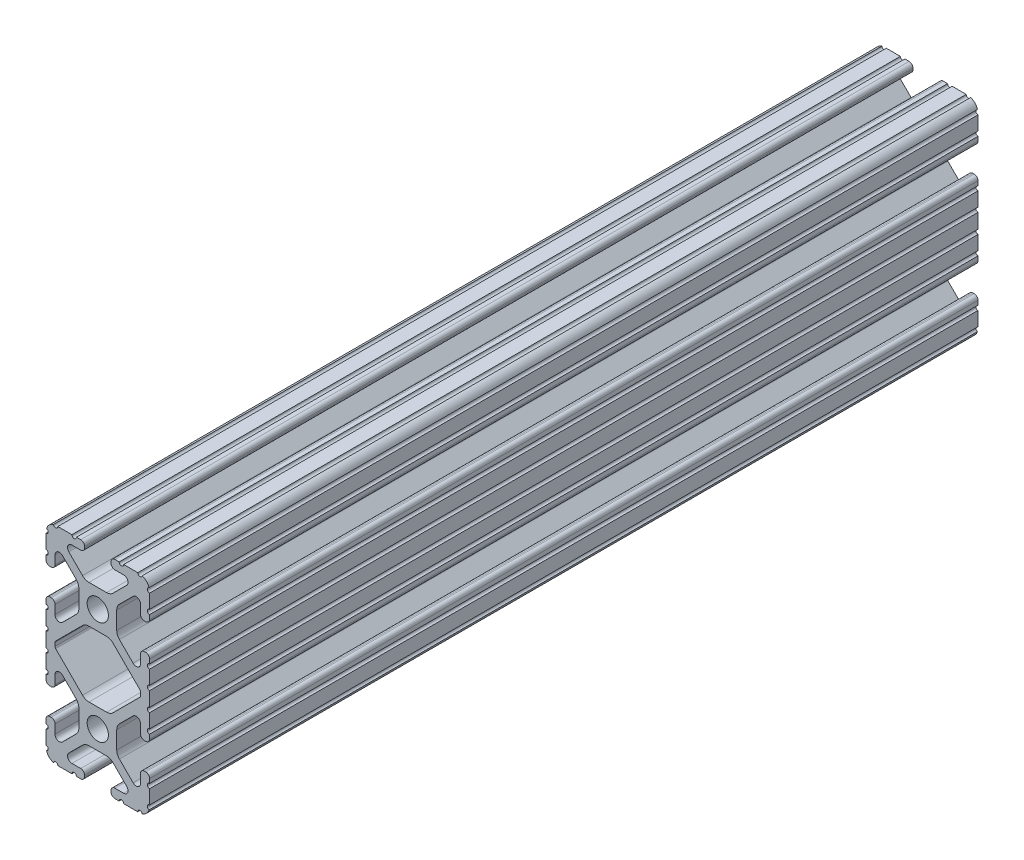
SolidWorks part; units mm, degrees
ref_plane "Front Plane" through (0, 0, 0) normal (0, 0, 1) x (1, 0, 0)
ref_plane "Top Plane" through (0, 0, 0) normal (0, 1, 0) x (1, 0, 0)
ref_plane "Right Plane" through (0, 0, 0) normal (1, 0, 0) x (0, 0, -1)
sketch "Sketch2" plane through (0, 0, 0) normal (0, 0, 1) x (1, 0, 0)
  line L0 (0, 25.4) -> (0, -25.4) construction
  line L1 (-12.7, 0) -> (12.7, 0) construction
  line L2 (3.2512, -25.4) -> (12.7, -25.4)
  line L3 (12.7, -25.4) -> (12.7, -15.9512)
  line L4 (3.2512, -25.4) -> (3.2512, -23.1902)
  line L5 (3.2512, -23.1902) -> (8.9276, -23.1902)
  line L6 (8.9276, -23.1902) -> (3.0856, -17.3482)
  line L7 (0, -12.7) -> (12.7, -25.4) construction
  line L8 (12.7, -15.9512) -> (10.4902, -15.9512)
  line L9 (10.4902, -15.9512) -> (10.4902, -21.6276)
  line L10 (10.4902, -21.6276) -> (4.6482, -15.7856)
  circle A0 centre (0, -12.7) radius 2.6035
  arc A1 (6.3485, -23.1902) -> (7.1039, -21.3665) centre (6.3485, -22.1219) ccw construction
  point P8 (0, -17.3482)
  dimension "Center Hole Diameter" = 5.207
  dimension "Rail Height" = 50.8
  dimension "Rail Width" = 25.4
  dimension "T-Slot Width" = 6.5024
  dimension "Slot Inner Width" = 14.8336
  dimension "Thickness" = 2.2098
  dimension "Slot Depth" = 5.842
  dimension "D1" = 2.2098
  dimension "C to C" = 25.4
sketch "Sketch3" plane through (0, 0, 0) normal (1, 0, 0) x (0, 0, -1)
  line L0 (-152.4, -25.4) -> (152.4, -25.4) construction
  line L1 (-127, 0) -> (127, 0) construction
  dimension "Length" = 304.8
  dimension "D1" = 25.4
sketch "Sketch4" plane through (0, 0, 0) normal (0, 0, 1) x (1, 0, 0)
  line L0 (4.1904, -25.4) -> (10.1173, -25.4)
  line L1 (3.2512, -25.4) -> (12.7, -25.4) construction
  line L2 (3.2512, -25.4) -> (3.2512, -23.1902) construction
  line L3 (3.2512, -23.1902) -> (8.9276, -23.1902) construction
  line L4 (3.2512, -24.1294) -> (3.2512, -24.4608)
  line L5 (4.1904, -23.1902) -> (6.3485, -23.1902)
  line L6 (0, -17.3482) -> (2.164, -17.3482)
  line L7 (8.9276, -23.1902) -> (3.0856, -17.3482) construction
  line L8 (3.7373, -17.9999) -> (7.1039, -21.3665)
  line L9 (12.7, -25.4) -> (12.7, -15.9512) construction
  line L10 (10.4902, -21.6276) -> (4.6482, -15.7856) construction
  line L11 (10.4902, -15.9512) -> (10.4902, -21.6276) construction
  line L12 (10.4902, -19.0485) -> (10.4902, -16.8904)
  line L13 (12.7, -15.9512) -> (10.4902, -15.9512) construction
  line L14 (11.4294, -15.9512) -> (11.7608, -15.9512)
  line L15 (12.7, -16.8904) -> (12.7, -22.8173)
  line L16 (8.6665, -19.8039) -> (5.2999, -16.4373)
  line L17 (4.6482, -12.7) -> (4.6482, -14.864)
  line L19 (0, -17.3482) -> (0, -15.3035)
  line L20 (0, 25.4) -> (0, -25.4) construction
  line L21 (4.6482, -12.7) -> (2.6035, -12.7)
  arc A0 (3.2512, -24.4608) -> (4.1904, -25.4) centre (4.1904, -24.4608) ccw
  circle A1 centre (0, -12.7) radius 2.6035 construction
  arc A2 (3.2512, -24.1294) -> (4.1904, -23.1902) centre (4.1904, -24.1294) cw
  arc A3 (6.3485, -23.1902) -> (7.1039, -21.3665) centre (6.3485, -22.1219) ccw
  arc A4 (2.164, -17.3482) -> (3.7373, -17.9999) centre (2.164, -19.5732) cw
  arc A5 (10.1173, -25.4) -> (12.7, -22.8173) centre (10.1173, -22.8173) ccw
  arc A6 (8.6665, -19.8039) -> (10.4902, -19.0485) centre (9.4219, -19.0485) ccw
  arc A7 (10.4902, -16.8904) -> (11.4294, -15.9512) centre (11.4294, -16.8904) cw
  arc A8 (11.7608, -15.9512) -> (12.7, -16.8904) centre (11.7608, -16.8904) cw
  arc A9 (5.2999, -16.4373) -> (4.6482, -14.864) centre (6.8732, -14.864) cw
  arc A11 (0, -15.3035) -> (2.6035, -12.7) centre (0, -12.7) ccw
  dimension "D1" = 2.5827
  dimension "D2" = 2.225
  dimension "D3" = 0.9392
extrude "Boss-Extrude1" add sketch "Sketch4" along normal mid plane 304.8
sketch "Sketch5" plane through (0, 0, 0) normal (0, 0, 1) x (1, 0, 0)
  line L0 (3.2512, -25.4) -> (12.7, -25.4) construction
  line L1 (4.1904, -23.1902) -> (6.3485, -23.1902) construction
  line L3 (0, -12.7) -> (12.7, -25.4) construction
  line L4 (6.3485, -23.1902) -> (6.3485, -25.4) construction
  line L5 (8.9276, -23.1902) -> (3.0856, -17.3482) construction
  circle A0 centre (10.3562, -25.4) radius 0.5524
  circle A1 centre (5.796, -25.4) radius 0.5524
  circle A2 centre (12.7, -23.0562) radius 0.5524
  circle A3 centre (12.7, -18.496) radius 0.5524
  point P10 (5.2694, -23.1902)
  point P12 (9.4219, -19.0485)
  dimension "D1" = 1.1049
extrude "Cut-Extrude1" cut sketch "Sketch5" against normal through all both and the other way through all
mirror "Mirror1" about plane through (4.6482, -12.7, 152.4) normal (0, -1, 0) of bodies 137 134
sketch "Sketch6" plane through (0, 0, 0) normal (0, 0, 1) x (1, 0, 0)
  line L0 (12.7, -1.7914) -> (12.7, 0)
  line L1 (12.7, 0) -> (9.8037, 0)
  line L2 (-12.7, 0) -> (12.7, 0) construction
  line L3 (9.8037, 0) -> (9.8037, -2.3438)
  line L4 (9.8037, -2.3438) -> (12.1476, -2.3438)
  circle A0 centre (12.7, -2.3438) radius 0.5524 construction
  arc A1 (12.7, -1.7914) -> (12.1476, -2.3438) centre (12.7, -2.3438) ccw
  arc A4 (12.58, -1.8046) -> (12.7, -2.8963) centre (12.7, -2.3438) ccw construction
  arc A6 (9.8037, 0) -> (10.8954, -0.12) centre (10.3562, 0) ccw construction
extrude "Boss-Extrude2" add sketch "Sketch6" along normal mid plane 304.8
sketch "Sketch7" plane through (0, 0, 0) normal (0, 0, 1) x (1, 0, 0)
  line L0 (5.4206, -5.7168) -> (10.3284, -0.809)
  line L1 (3.7373, -7.4001) -> (7.1039, -4.0335) construction
  line L2 (10.4902, -0.4184) -> (10.4902, 0)
  line L3 (0, 0) -> (10.4902, 0)
  line L4 (-12.7, 0) -> (12.7, 0) construction
  line L5 (0, 0) -> (5.4206, -5.7168)
  arc A0 (10.3284, -0.809) -> (10.4902, -0.4184) centre (9.9377, -0.4184) ccw
  arc A3 (12.7, -1.7914) -> (12.7, -2.8963) centre (12.7, -2.3438) ccw construction
extrude "Cut-Extrude2" cut sketch "Sketch7" against normal through all both and the other way through all
mirror "Mirror2" about plane through (0, 0, 0) normal (0, 1, 0) of bodies 139 135
mirror "Mirror3" about plane through (0, 0, 0) normal (1, 0, 0) of bodies 136
sketch "Sketch8" plane through (12.7, 0, 0) normal (1, 0, 0) x (0, 0, -1)
  line L0 (152.4, -25.4) -> (-152.4, -25.4) construction
  line L1 (-152.4, 25.4) -> (-101.6, 25.4)
  line L2 (-152.4, 25.4) -> (-152.4, -25.4)
  line L3 (-152.4, -25.4) -> (-101.6, -25.4)
  line L4 (-101.6, 25.4) -> (-101.6, -25.4)
  line L5 (152.4, 25.4) -> (-152.4, 25.4) construction
  line L6 (152.4, -25.4) -> (101.6, -25.4)
  line L7 (152.4, -25.4) -> (152.4, 25.4)
  line L8 (152.4, 25.4) -> (101.6, 25.4)
  line L9 (101.6, -25.4) -> (101.6, 25.4)
  dimension "D1" = 50.8
  dimension "D2" = 50.8
extrude "Cut-Extrude3" cut sketch "Sketch8" against normal through all
equation "\"D1@Boss-Extrude1\"=\"Length@Sketch3\""
equation "\"D1@Sketch2\"=\"Thickness@Sketch2\""
equation "\"D2@Sketch4\"=\"Slot Inner Width@Sketch2\"*0.15"
equation "\"D1@Sketch4\"=\"D3@Sketch4\"*2.75"
equation "\"D3@Sketch4\"=\"Thickness@Sketch2\"*0.425"
equation "\"D1@Sketch5\"=\"Thickness@Sketch2\"*0.5"
equation "\"D1@Boss-Extrude2\"=\"Length@Sketch3\""
